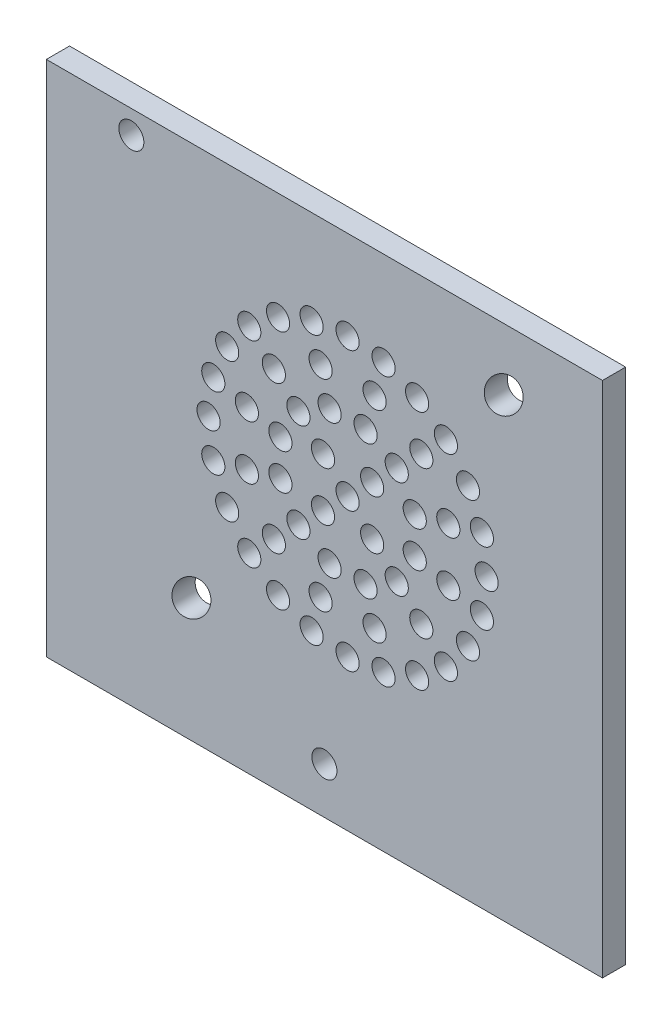
SolidWorks part; units mm, degrees
ref_plane "Alzado" through (0, 0, 0) normal (0, 0, 1) x (1, 0, 0)
ref_plane "Planta" through (0, 0, 0) normal (0, 1, 0) x (1, 0, 0)
ref_plane "Vista lateral" through (0, 0, 0) normal (1, 0, 0) x (0, 0, -1)
sketch "Croquis1" plane through (0, 0, 0) normal (0, 0, 1) x (1, 0, 0)
  line B0 (158.25, 25.0563) -> (86.25, 25.0563)
  line B1 (86.25, 25.0563) -> (86.25, -41.9437)
  line B2 (86.25, -41.9437) -> (158.25, -41.9437)
  line B3 (158.25, -41.9437) -> (158.25, 25.0563)
sketch_block_instance "Bloque-Croquis2-1"
sketch_block "Bloque-Croquis2" parameters "D1"=50, "D2"=14, "D3"=10.5
extrude "Saliente-Extruir1" add sketch "Croquis1" along normal blind 3
sketch "Croquis3" plane through (0, 0, 0) normal (0, 0, -1) x (-1, 0, 0)
  line L0 (-158.25, -8.4437) -> (-86.25, -8.4437) construction
  line L9 (-122.25, 25.0563) -> (-122.25, -41.9437) construction
  line L10 (-158.25, -41.9437) -> (-158.25, 25.0563) construction
  line L11 (-86.25, 25.0563) -> (-86.25, -41.9437) construction
  line L12 (-125.25, 25.0563) -> (-125.25, -41.9437) construction
  line L13 (-158.25, -4.4437) -> (-86.25, -4.4437) construction
  line L14 (-158.25, -41.9437) -> (-158.25, 25.0563) construction
  line L25 (-158.25, 25.0563) -> (-86.25, 25.0563) construction
  line L26 (-86.25, -41.9437) -> (-158.25, -41.9437) construction
  circle A0 centre (-122.25, -35.9437) radius 1.625 construction
  circle A2 centre (-122.25, -35.9437) radius 1.625
  circle A3 centre (-122.25, 22.0563) radius 1.625 construction
  circle A5 centre (-97.25, 22.0563) radius 1.625
  point P10 (0, 0)
  point P11 (-125.25, -4.4437)
  point P15 (0, 0)
  point P24 (-97.25, 10.9525)
  point P26 (0, 0)
  point P27 (0, 0)
  circle B0 centre (-141.1599, -20.3536) radius 1.5 construction
  circle B1 centre (-141.1599, 11.4662) radius 1.5 construction
  circle B2 centre (-137.9779, 8.2842) radius 1.5
  circle B3 centre (-129.9087, 12.943) radius 1.5
  circle B4 centre (-134.25, 11.1448) radius 1.5
  circle B5 centre (-128.7441, 8.5963) radius 1.5
  circle B6 centre (-125.25, 13.5563) radius 1.5
  circle B7 centre (-120.5913, 12.943) radius 1.5
  circle B8 centre (-121.7559, 8.5963) radius 1.5
  circle B9 centre (-116.25, 11.1448) radius 1.5
  circle B10 centre (-109.3401, 11.4662) radius 1.5 construction
  circle B11 centre (-112.5221, 8.2842) radius 1.5
  circle B12 centre (-115.7041, 5.1022) radius 1.5
  circle B13 centre (-109.6615, 4.5563) radius 1.5
  circle B14 centre (-107.25, -4.4437) radius 1.5
  circle B15 centre (-107.8633, 0.215) radius 1.5
  circle B16 centre (-112.21, -0.9496) radius 1.5
  circle B17 centre (-116.5567, -2.1143) radius 1.5
  circle B18 centre (-118.886, 1.9203) radius 1.5
  circle B19 centre (-122.068, -1.2617) radius 1.5
  circle B20 centre (-122.9206, 4.2496) radius 1.5
  circle B21 centre (-127.5794, 4.2496) radius 1.5
  circle B22 centre (-131.614, 1.9203) radius 1.5
  circle B23 centre (-128.432, -1.2617) radius 1.5
  circle B24 centre (-134.7959, 5.1022) radius 1.5
  circle B25 centre (-140.8385, 4.5563) radius 1.5
  circle B26 centre (-143.25, -4.4437) radius 1.5
  circle B27 centre (-142.6367, 0.215) radius 1.5
  circle B28 centre (-138.29, -0.9496) radius 1.5
  circle B29 centre (-133.9433, -2.1143) radius 1.5
  circle B30 centre (-133.9433, -6.7731) radius 1.5
  circle B31 centre (-125.25, -4.4437) radius 1.5
  circle B32 centre (-128.432, -7.6257) radius 1.5
  circle B33 centre (-122.068, -7.6257) radius 1.5
  circle B34 centre (-116.5567, -6.7731) radius 1.5
  circle B35 centre (-107.8633, -9.1024) radius 1.5
  circle B36 centre (-112.21, -7.9378) radius 1.5
  circle B37 centre (-109.6615, -13.4437) radius 1.5
  circle B38 centre (-109.3401, -20.3536) radius 1.5 construction
  circle B39 centre (-112.5221, -17.1716) radius 1.5
  circle B40 centre (-118.886, -10.8077) radius 1.5
  circle B41 centre (-127.5794, -13.137) radius 1.5
  circle B42 centre (-122.9206, -13.137) radius 1.5
  circle B43 centre (-115.7041, -13.9896) radius 1.5
  circle B44 centre (-121.7559, -17.4837) radius 1.5
  circle B45 centre (-116.25, -20.0322) radius 1.5
  circle B46 centre (-120.5913, -21.8304) radius 1.5
  circle B47 centre (-125.25, -22.4437) radius 1.5
  circle B48 centre (-128.7441, -17.4837) radius 1.5
  circle B49 centre (-131.614, -10.8077) radius 1.5
  circle B50 centre (-134.7959, -13.9896) radius 1.5
  circle B51 centre (-138.29, -7.9378) radius 1.5
  circle B52 centre (-142.6367, -9.1024) radius 1.5
  circle B53 centre (-140.8385, -13.4437) radius 1.5
  circle B54 centre (-137.9779, -17.1716) radius 1.5
  circle B55 centre (-134.25, -20.0322) radius 1.5
  circle B56 centre (-129.9087, -21.8304) radius 1.5
  ellipse B57 centre (-145.4647, 17.0416) end of major axis (-143.4089, 14.8566) minor radius 2
  ellipse B58 centre (-104.3903, 16.4159) end of major axis (-106.4945, 14.2776) minor radius 2 construction
  ellipse B59 centre (-105.0353, -25.929) end of major axis (-102.9796, -28.1139) minor radius 2
  ellipse B60 centre (-146.1097, -25.3034) end of major axis (-148.231, -27.4247) minor radius 2 construction
  dimension "D5" = 3.25
  dimension "D6" = 3
  dimension "D1" = 4
  dimension "D2" = 3
  dimension "D4" = 11
sketch_block_instance "Bloque1-1"
sketch_block "Bloque1"
extrude "Cortar-Extruir1" cut sketch "Croquis3" against normal blind 3
